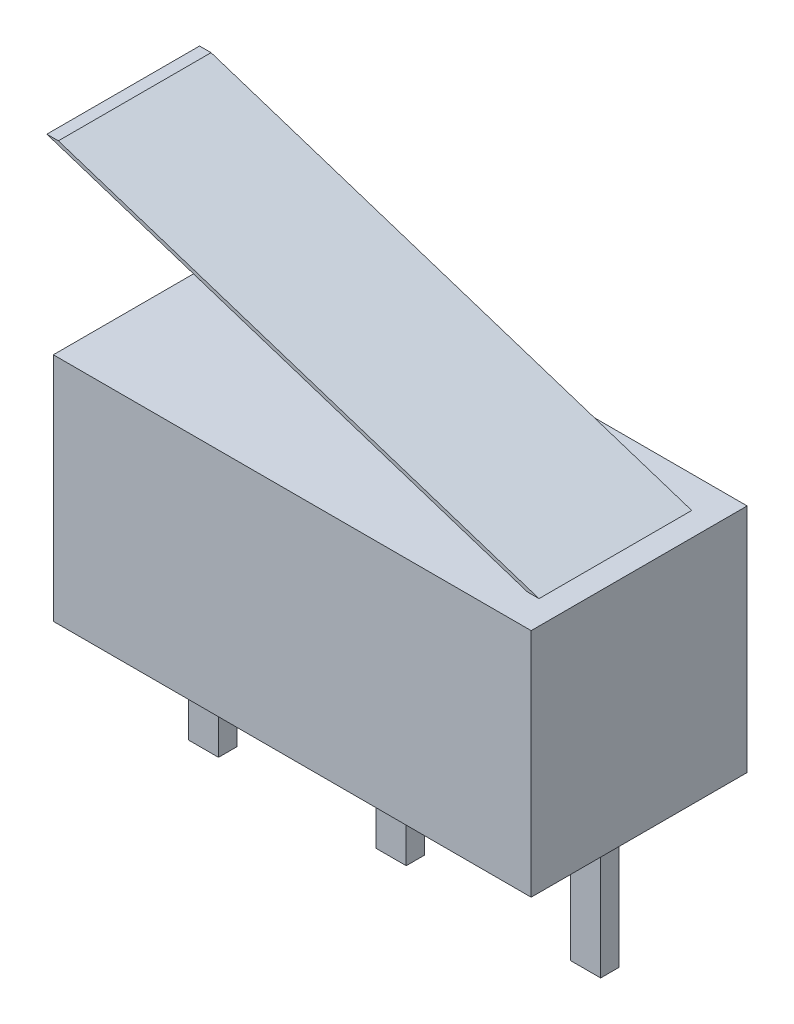
SolidWorks part; units mm, degrees
ref_plane "Front Plane" through (0, 0, 0) normal (0, 0, 1) x (1, 0, 0)
ref_plane "Top Plane" through (0, 0, 0) normal (0, 1, 0) x (1, 0, 0)
ref_plane "Right Plane" through (0, 0, 0) normal (1, 0, 0) x (0, 0, -1)
sketch "Sketch1" plane through (0, 0, 0) normal (0, 1, 0) x (1, 0, 0)
  line L1 (-6.415, -2.9) -> (6.415, -2.9)
  line L2 (-6.415, -2.9) -> (-6.415, 2.9)
  line L3 (-6.415, 2.9) -> (6.415, 2.9)
  line L4 (6.415, -2.9) -> (6.415, 2.9)
  line L5 (-6.415, -2.9) -> (6.415, 2.9) construction
  line L6 (-6.415, 2.9) -> (6.415, -2.9) construction
  point P0 (0, 0)
  dimension "D1" = 5.8
  dimension "D2" = 12.83
extrude "Boss-Extrude1" add sketch "Sketch1" along normal blind 6.2
sketch "Sketch2" plane through (0, 6.2, 0) normal (0, 1, 0) x (1, 0, 0)
  line L1 (5.4662, 2.05) -> (5.7762, 2.05)
  line L2 (5.4662, 2.05) -> (5.4662, -2.05)
  line L3 (5.4662, -2.05) -> (5.7762, -2.05)
  line L4 (5.7762, 2.05) -> (5.7762, -2.05)
  line L5 (5.4662, 2.05) -> (5.7762, -2.05) construction
  line L6 (5.4662, -2.05) -> (5.7762, 2.05) construction
  point P0 (5.6212, 0)
  point P5 (0, 0)
  dimension "D1" = 4.1
  dimension "D2" = 0.31
sketch "Sketch3" plane through (0, 0, 2.9) normal (0, 0, 1) x (1, 0, 0)
  line L0 (5.6212, 6.2) -> (-7.2849, 10.3926)
  line L1 (-6.415, 6.2) -> (-6.415, 10.11) construction
  point P6 (-7.0973, 10.7682)
  point P7 (-6.415, 10.5232)
  dimension "D1" = 3.91
  dimension "D2" = 13.57
sweep "Sweep1" add profiles "Sketch2" path "Sketch3"
sketch "Sketch4" plane through (0, 0, 0) normal (0, -1, 0) x (1, 0, 0)
  line L0 (-6.415, -2.9) -> (-6.415, 2.9) construction
  line L1 (-5.445, -0.245) -> (-4.635, -0.245)
  line L2 (-5.445, -0.245) -> (-5.445, 0.245)
  line L3 (-5.445, 0.245) -> (-4.635, 0.245)
  line L4 (-4.635, -0.245) -> (-4.635, 0.245)
  line L5 (-5.445, -0.245) -> (-4.635, 0.245) construction
  line L6 (-5.445, 0.245) -> (-4.635, -0.245) construction
  line L7 (-0.405, -0.245) -> (0.405, -0.245)
  line L8 (-0.405, -0.245) -> (-0.405, 0.245)
  line L9 (-0.405, 0.245) -> (0.405, 0.245)
  line L10 (0.405, -0.245) -> (0.405, 0.245)
  line L11 (-0.405, -0.245) -> (0.405, 0.245) construction
  line L12 (-0.405, 0.245) -> (0.405, -0.245) construction
  line L13 (4.8159, -0.245) -> (5.6259, -0.245)
  line L14 (4.8159, -0.245) -> (4.8159, 0.245)
  line L15 (4.8159, 0.245) -> (5.6259, 0.245)
  line L16 (5.6259, -0.245) -> (5.6259, 0.245)
  line L17 (4.8159, -0.245) -> (5.6259, 0.245) construction
  line L18 (4.8159, 0.245) -> (5.6259, -0.245) construction
  point P0 (-5.04, 0)
  point P5 (0, 0)
  point P11 (5.2209, 0)
  point P18 (0, 0)
  dimension "D1" = 0.97
  dimension "D2" = 0.81
  dimension "D3" = 0.49
extrude "Boss-Extrude2" add sketch "Sketch4" along normal blind 3.6
